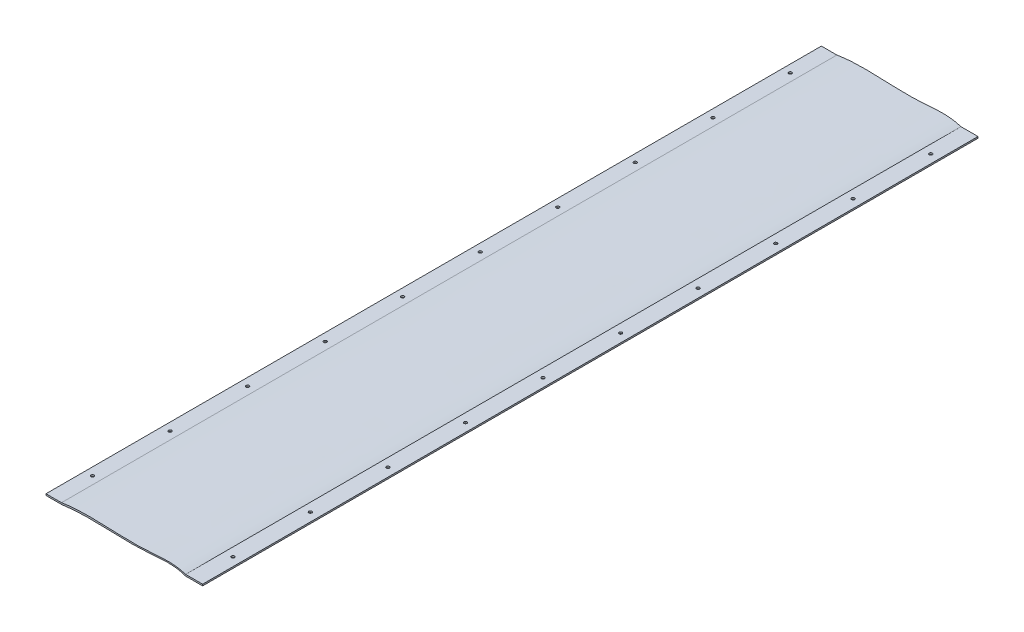
SolidWorks part; units mm, degrees
material "Polyester Resin"
ref_plane "Front Plane" through (0, 0, 0) normal (0, 0, 1) x (1, 0, 0)
ref_plane "Top Plane" through (0, 0, 0) normal (0, 1, 0) x (1, 0, 0)
ref_plane "Right Plane" through (0, 0, 0) normal (1, 0, 0) x (0, 0, -1)
sketch "Sketch1" plane through (0, 0, 0) normal (0, 0, 1) x (1, 0, 0)
  line L1 (-100, 0) -> (-100, 2)
  line L2 (102, 0) -> (102, 2)
  line L3 (-100, 2) -> (-80, 2)
  line L4 (102, 2) -> (80, 2)
  line L5 (-100, 0) -> (-80, 0)
  line L6 (102, 0) -> (80, 0)
  spline S0 degree 3 poles (-80, 2) (-43.5921, 8.0406) (9.7386, -1.4683) (63.3343, 7.5349) (80, 2) knots 0 0 0 0 0.681211 1 1 1 1
  spline S1 degree 3 poles (-80, 0) (-43.5719, 5.4024) (9.7391, -3.2528) (63.4152, 6.1771) (80, 0) knots 0 0 0 0 0.680839 1 1 1 1
  point P4 (0, 0)
extrude "Boss-Extrude1" add sketch "Sketch1" against normal blind 1000
sketch "Sketch2" plane through (0, 2, 0) normal (0, 1, 0) x (1, 0, 0)
  line L0 (102, 1000) -> (80, 1000) construction
  circle A0 centre (91, 950) radius 2
  circle A1 centre (-90, 950) radius 2
  circle A2 centre (91, 850) radius 2
  circle A3 centre (-90, 850) radius 2
  circle A4 centre (91, 750) radius 2
  circle A5 centre (-90, 750) radius 2
  circle A6 centre (91, 650) radius 2
  circle A7 centre (-90, 650) radius 2
  circle A8 centre (91, 550) radius 2
  circle A9 centre (-90, 550) radius 2
  circle A10 centre (91, 450) radius 2
  circle A11 centre (-90, 450) radius 2
  circle A12 centre (91, 350) radius 2
  circle A13 centre (-90, 350) radius 2
  circle A14 centre (91, 250) radius 2
  circle A15 centre (-90, 250) radius 2
  circle A16 centre (91, 150) radius 2
  circle A17 centre (-90, 150) radius 2
  circle A18 centre (91, 50) radius 2
  circle A19 centre (-90, 50) radius 2
  dimension "D1" = 50
  dimension "D2" = 10
extrude "Cut-Extrude1" cut sketch "Sketch2" against normal blind 1000
